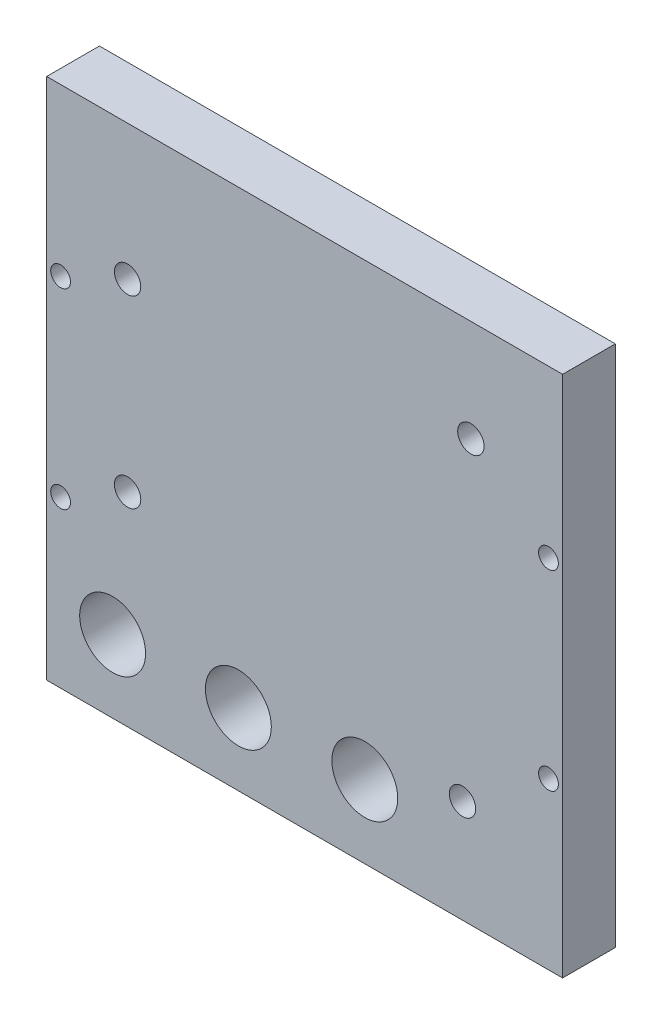
SolidWorks part; units mm, degrees
ref_plane "Front Plane" through (0, 0, 0) normal (0, 0, 1) x (1, 0, 0)
ref_plane "Top Plane" through (0, 0, 0) normal (0, 1, 0) x (1, 0, 0)
ref_plane "Right Plane" through (0, 0, 0) normal (1, 0, 0) x (0, 0, -1)
sketch "Sketch1" plane through (0, 0, 0) normal (0, 0, 1) x (1, 0, 0)
  line L0 (-38.9489, 40.0022) -> (39.3011, 40.0022)
  line L1 (39.3011, 40.0022) -> (39.3011, -39.2978)
  line L2 (-38.9489, 40.0022) -> (-38.9489, -39.2978)
  line L3 (-38.9489, -39.2978) -> (39.3011, -39.2978)
  circle A0 centre (-9.8752, -28.3944) radius 5
  circle A1 centre (9.3011, -28.2174) radius 5
  circle A2 centre (-28.9489, -28.3036) radius 5
  circle A3 centre (-26.6773, 19.5022) radius 2
  circle A4 centre (-26.6773, -8.4378) radius 2
  circle A5 centre (24.1227, -23.6778) radius 2
  circle A6 centre (25.3927, 24.5822) radius 2
  circle A7 centre (-36.8377, 14.8141) radius 1.5
  circle A8 centre (-36.8377, -14.1859) radius 1.5
  circle A9 centre (37.1623, -14.1859) radius 1.5
  circle A10 centre (37.1623, 14.8141) radius 1.5
extrude "Boss-Extrude1" add sketch "Sketch1" along normal blind 8
